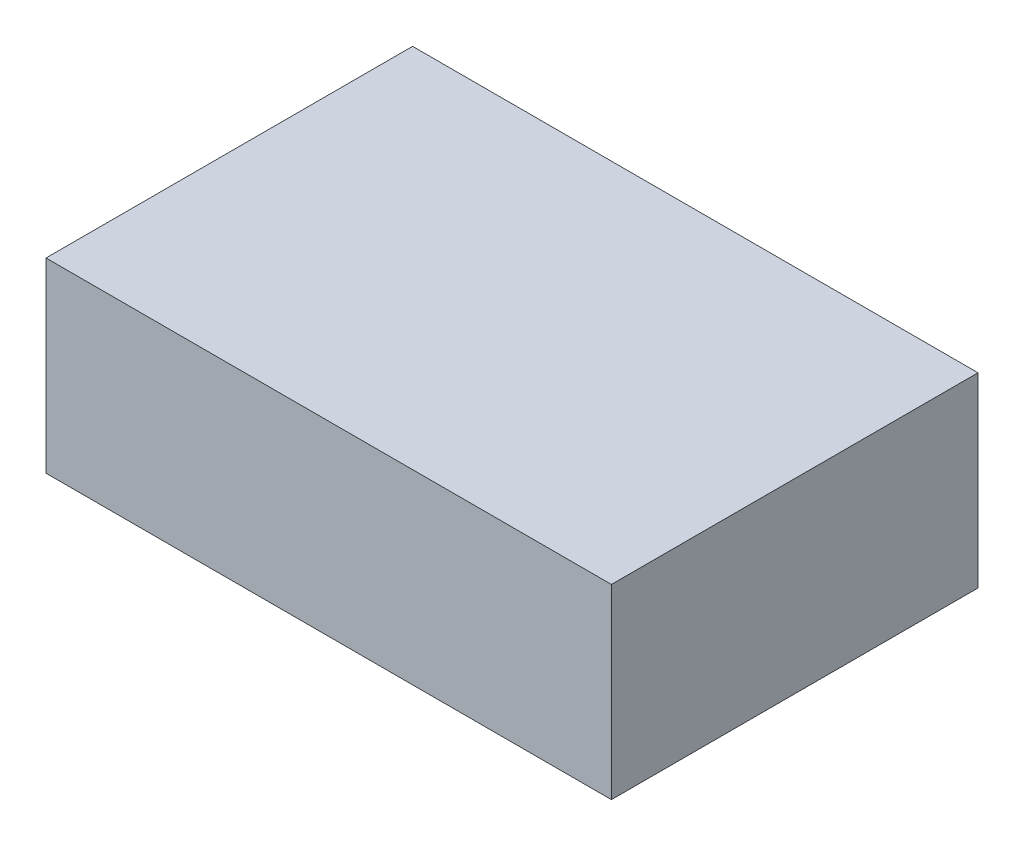
SolidWorks part; units mm, degrees
ref_plane "Front Plane" through (0, 0, 0) normal (0, 0, 1) x (1, 0, 0)
ref_plane "Top Plane" through (0, 0, 0) normal (0, 1, 0) x (1, 0, 0)
ref_plane "Right Plane" through (0, 0, 0) normal (1, 0, 0) x (0, 0, -1)
sketch "Sketch1" plane through (0, 0, 0) normal (0, 1, 0) x (1, 0, 0)
  line L1 (0, 0) -> (91, 0)
  line L2 (0, 0) -> (0, 59)
  line L3 (0, 59) -> (91, 59)
  line L4 (91, 0) -> (91, 59)
  dimension "D1" = 91
  dimension "D2" = 59
extrude "Boss-Extrude1" add sketch "Sketch1" along normal blind 30
